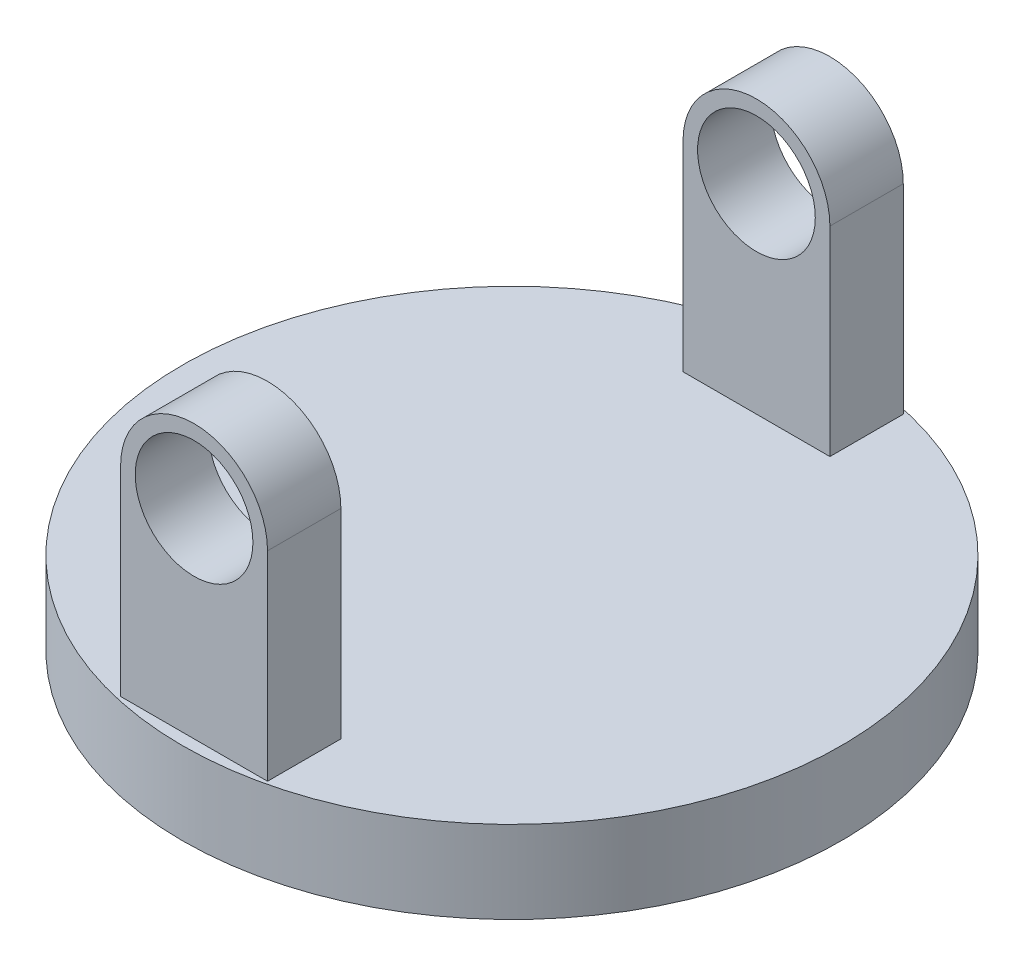
SolidWorks part; units mm, degrees
other "Markup1"
sketch "Sketch5" plane through (28, 21.7091, 28) normal (0.6305, 0.646, 0.4304) x (0.4486, 0.1493, -0.8812)
ref_plane "Front Plane" through (0, 0, 0) normal (0, 0, 1) x (1, 0, 0)
ref_plane "Top Plane" through (0, 0, 0) normal (0, 1, 0) x (1, 0, 0)
ref_plane "Right Plane" through (0, 0, 0) normal (1, 0, 0) x (0, 0, -1)
sketch "Sketch1" plane through (0, 0, 0) normal (0, 1, 0) x (1, 0, 0)
  circle A0 centre (0, 0) radius 28
extrude "Boss-Extrude1" add sketch "Sketch1" along normal blind 7
ref_plane "Plane1" through (0, 0, 22) normal (0, 0, 1) x (1, 0, 0)
sketch "Sketch4" plane through (0, 0, 22) normal (0, 0, 1) x (1, 0, 0)
  line L1 (28, 7) -> (-28, 7) construction
  line L6 (-6.2415, 15.4676) -> (-6.2415, 7)
  line L7 (-6.2415, 15.4676) -> (-6.2415, 23.9565)
  line L8 (6.2415, 15.4676) -> (6.2415, 7)
  line L9 (6.2415, 7) -> (5, 7)
  line L11 (6.2415, 23.9565) -> (6.2415, 15.4676)
  arc A0 (2.6429, 19.7121) -> (-2.6429, 19.7121) centre (0, 15.4676) ccw
  arc A2 (-6.2415, 7) -> (6.2415, 7) centre (0, 25.4063) ccw
  arc A3 (6.2415, 23.9565) -> (-6.2415, 23.9565) centre (0, 23.9565) ccw
  circle A4 centre (0, 23.9565) radius 5
extrude "Boss-Extrude2" add sketch "Sketch4" against normal blind 1.2265 and the other way blind 5.0059
mirror "Mirror1" about plane through (0, 0, 0) normal (0, 0, 1) of "Boss-Extrude2"
